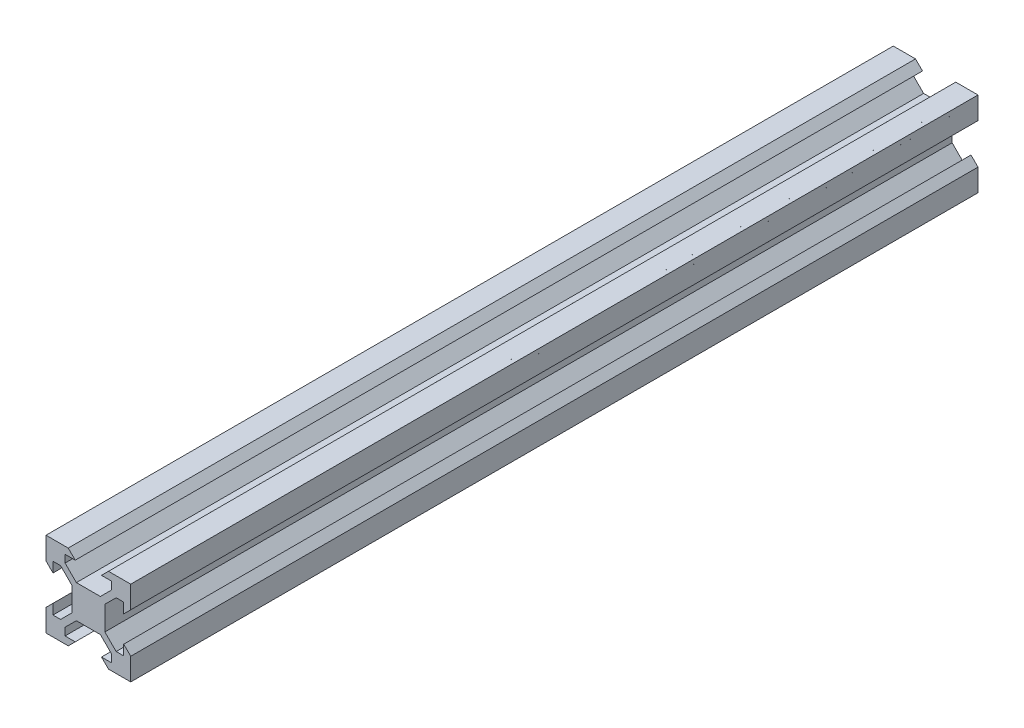
SolidWorks part; units mm, degrees
ref_plane "Front Plane" through (0, 0, 0) normal (0, 0, 1) x (1, 0, 0)
ref_plane "Top Plane" through (0, 0, 0) normal (0, 1, 0) x (1, 0, 0)
ref_plane "Right Plane" through (0, 0, 0) normal (1, 0, 0) x (0, 0, -1)
sketch "Sketch1" plane through (0, 0, 0) normal (0, 0, 1) x (1, 0, 0)
  line L88 (2.8343, 3.894) -> (-2.8343, 3.894)
  line L89 (-2.8343, 3.894) -> (-5.5, 6.5588)
  line L90 (-5.5, 6.5588) -> (-5.5, 8.3491)
  line L91 (-5.5, 8.3491) -> (-3.1, 8.3491)
  line L92 (-3.1, 8.3491) -> (-4.75, 9.9986)
  line L93 (-4.75, 9.9986) -> (-10, 9.9986)
  line L94 (-10, 9.9986) -> (-10, 4.747)
  line L95 (-10, 4.747) -> (-8.35, 3.0975)
  line L96 (-8.35, 3.0975) -> (-8.3507, 5.4975)
  line L97 (-8.3507, 5.4975) -> (-6.5605, 5.498)
  line L98 (-6.5605, 5.498) -> (-3.8948, 2.8332)
  line L99 (-3.8948, 2.8332) -> (-3.8948, -2.8332)
  line L100 (-3.8948, -2.8332) -> (-6.5605, -5.498)
  line L101 (-6.5605, -5.498) -> (-8.3507, -5.4975)
  line L102 (-8.3507, -5.4975) -> (-8.35, -3.0975)
  line L103 (-8.35, -3.0975) -> (-10, -4.747)
  line L104 (-10, -4.747) -> (-10, -9.9986)
  line L105 (-10, -9.9986) -> (-4.75, -9.9986)
  line L106 (-4.75, -9.9986) -> (-3.1, -8.3491)
  line L107 (-3.1, -8.3491) -> (-5.5, -8.3491)
  line L108 (-5.5, -8.3491) -> (-5.5, -6.5588)
  line L109 (-5.5, -6.5588) -> (-2.8343, -3.894)
  line L110 (-2.8343, -3.894) -> (2.8343, -3.894)
  line L111 (2.8343, -3.894) -> (5.5, -6.5588)
  line L112 (5.5, -6.5588) -> (5.5, -8.3491)
  line L113 (5.5, -8.3491) -> (3.1, -8.3491)
  line L114 (3.1, -8.3491) -> (4.75, -9.9986)
  line L115 (4.75, -9.9986) -> (10, -9.9986)
  line L116 (10, -9.9986) -> (10, -4.747)
  line L117 (10, -4.747) -> (8.35, -3.0975)
  line L118 (8.35, -3.0975) -> (8.3507, -5.4975)
  line L119 (8.3507, -5.4975) -> (6.5605, -5.498)
  line L120 (6.5605, -5.498) -> (3.8948, -2.8332)
  line L121 (3.8948, -2.8332) -> (3.8948, 2.8332)
  line L122 (3.8948, 2.8332) -> (6.5605, 5.498)
  line L123 (6.5605, 5.498) -> (8.3507, 5.4975)
  line L124 (8.3507, 5.4975) -> (8.35, 3.0975)
  line L125 (8.35, 3.0975) -> (10, 4.747)
  line L126 (10, 4.747) -> (10, 9.9986)
  line L127 (10, 9.9986) -> (4.75, 9.9986)
  line L128 (4.75, 9.9986) -> (3.1, 8.3491)
  line L129 (3.1, 8.3491) -> (5.5, 8.3491)
  line L130 (5.5, 8.3491) -> (5.5, 6.5588)
  line L131 (5.5, 6.5588) -> (2.8343, 3.894)
  dimension "D2" = 5.25
  dimension "D3" = 19.9971
  dimension "D4" = 20
extrude "Boss-Extrude1" add sketch "Sketch1" along normal blind 200
